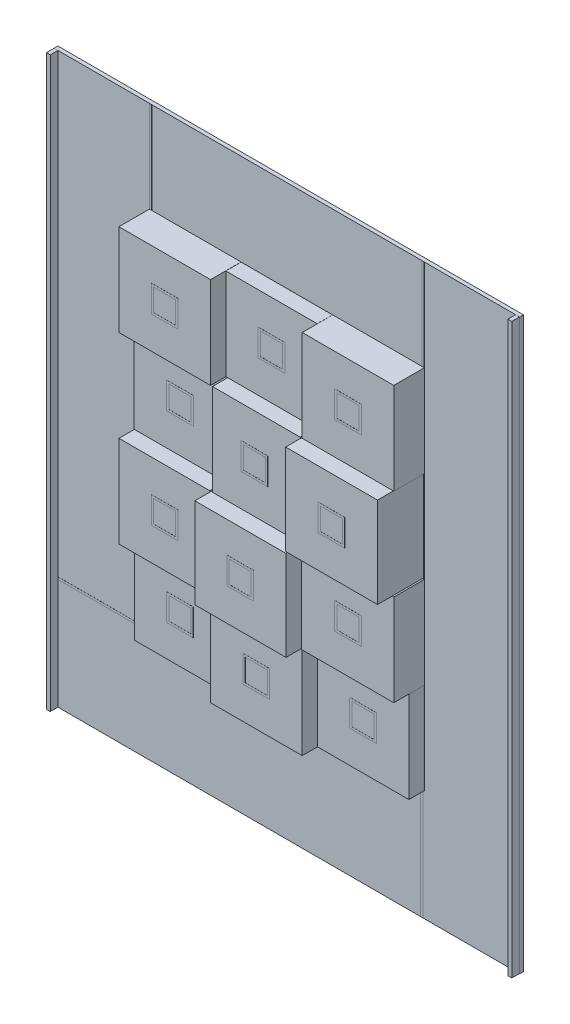
SolidWorks part; units mm, degrees
material "Teak"
ref_plane "Front Plane" through (0, 0, 0) normal (0, 0, 1) x (1, 0, 0)
ref_plane "Top Plane" through (0, 0, 0) normal (0, 1, 0) x (1, 0, 0)
ref_plane "Right Plane" through (0, 0, 0) normal (1, 0, 0) x (0, 0, -1)
sketch "Sketch1" plane through (0, 0, 0) normal (0, 0, 1) x (1, 0, 0)
  line L1 (-2918.6486, 3349.1441) -> (3181.3514, 3349.1441)
  line L2 (-2918.6486, 3349.1441) -> (-2918.6486, -4100.8559)
  line L3 (-2918.6486, -4100.8559) -> (3181.3514, -4100.8559)
  line L4 (3181.3514, 3349.1441) -> (3181.3514, -4100.8559)
  dimension "D1" = 7450
  dimension "D2" = 6100
extrude "Boss-Extrude1" add sketch "Sketch1" along normal blind 50
sketch "Sketch5" plane through (0, 0, 50) normal (0, 0, 1) x (1, 0, 0)
  line L1 (-1668.6486, -2650.8559) -> (1931.3514, -2650.8559)
  line L2 (-1668.6486, -2650.8559) -> (-1668.6486, 2149.1441)
  line L3 (-1668.6486, 2149.1441) -> (1931.3514, 2149.1441)
  line L4 (1931.3514, -2650.8559) -> (1931.3514, 2149.1441)
  line L8 (-1618.6486, -2600.8559) -> (-1618.6486, 2099.1441)
  line L9 (-1618.6486, 2099.1441) -> (1881.3514, 2099.1441)
  line L10 (1881.3514, -2600.8559) -> (1881.3514, 2099.1441)
  line L11 (-1618.6486, -2600.8559) -> (1881.3514, -2600.8559)
  dimension "D1" = 3600
  dimension "D2" = 4800
  dimension "D3" = 50
extrude "Boss-Extrude6" add sketch "Sketch5" along normal blind 1
sketch "Sketch7" plane through (0, 0, 50) normal (0, 0, 1) x (1, 0, 0)
  line L0 (-1668.6486, -2650.8559) -> (1931.3514, -2650.8559) construction
  line L1 (-1668.6486, 2149.1441) -> (-468.6486, 2149.1441)
  line L2 (-1668.6486, 2149.1441) -> (-1668.6486, 949.1441)
  line L3 (-1668.6486, 949.1441) -> (-468.6486, 949.1441)
  line L4 (-468.6486, 2149.1441) -> (-468.6486, 949.1441)
  line L5 (1931.3514, 2149.1441) -> (731.3514, 2149.1441)
  line L6 (1931.3514, 2149.1441) -> (1931.3514, 949.1441)
  line L7 (1931.3514, 949.1441) -> (731.3514, 949.1441)
  line L8 (731.3514, 2149.1441) -> (731.3514, 949.1441)
  line L9 (-443.6486, 949.1441) -> (706.3514, 949.1441)
  line L10 (-443.6486, 949.1441) -> (-443.6486, -250.8559)
  line L11 (-443.6486, -250.8559) -> (706.3514, -250.8559)
  line L12 (706.3514, 949.1441) -> (706.3514, -250.8559)
  line L13 (-468.6486, -2650.8559) -> (731.3514, -2650.8559)
  line L14 (-468.6486, -2650.8559) -> (-468.6486, -1450.8559)
  line L15 (-468.6486, -1450.8559) -> (731.3514, -1450.8559)
  line L16 (731.3514, -2650.8559) -> (731.3514, -1450.8559)
  line L17 (1931.3514, -2650.8559) -> (1931.3514, 2149.1441) construction
  line L18 (-1668.6486, 2149.1441) -> (-1668.6486, -2650.8559) construction
  line L19 (-1668.6486, -250.8559) -> (-478.6486, -250.8559)
  line L20 (-1668.6486, -250.8559) -> (-1668.6486, -1450.8559)
  line L21 (-1668.6486, -1450.8559) -> (-478.6486, -1450.8559)
  line L22 (-478.6486, -250.8559) -> (-478.6486, -1450.8559)
  line L24 (1931.3514, -250.8559) -> (721.3514, -250.8559)
  line L25 (1931.3514, -250.8559) -> (1931.3514, -1450.8559)
  line L26 (1931.3514, -1450.8559) -> (721.3514, -1450.8559)
  line L27 (721.3514, -250.8559) -> (721.3514, -1450.8559)
  line M34 (1931.3514, -2650.8559) -> (-1668.6486, -2650.8559)
  line M35 (-1668.6486, -2650.8559) -> (-1668.6486, 2149.1441)
  line M36 (-1668.6486, 2149.1441) -> (1931.3514, 2149.1441)
  line M37 (1931.3514, 2149.1441) -> (1931.3514, -2650.8559)
  dimension "D1" = 1200
  dimension "D2" = 1200
  dimension "D3" = 1200
  dimension "D4" = 1200
  dimension "D5" = 0
  dimension "D6" = 1200
  dimension "D7" = 1150
  dimension "D8" = 25
  dimension "D9" = 1200
  dimension "D10" = 1200
  dimension "D11" = 1200
  dimension "D12" = 1190
  dimension "D13" = 1200
  dimension "D14" = 1200
  dimension "D15" = 1210
extrude "Boss-Extrude11" add sketch "Sketch7" along normal blind 400 contours L4 L3 M36 M35 | L8 L7 M36 M37 | L12 L9 L10 L11 | L22 L19 L21 M35 | L16 L15 L14 M34 | L24 L27 L15 L26 M37
sketch "Sketch10" plane through (0, 0, 51) normal (0, 0, 1) x (1, 0, 0)
  line L0 (-468.6486, -2600.8559) -> (-468.6486, -1450.8559) construction
  line L1 (-1664.9685, -1454.3725) -> (-471.6486, -1454.3725)
  line L2 (-1664.9685, -1454.3725) -> (-1664.9685, -2638.6722)
  line L3 (-1664.9685, -2638.6722) -> (-471.6486, -2638.6722)
  line L4 (-471.6486, -1454.3725) -> (-471.6486, -2638.6722)
  dimension "D1" = 1184.2997
  dimension "D2" = 1193.3199
  dimension "D3" = 3
extrude "Boss-Extrude13" add sketch "Sketch10" along normal blind 200
sketch "Sketch11" plane through (0, 0, 51) normal (0, 0, 1) x (1, 0, 0)
  line L1 (1928.9649, -1452.6084) -> (732.4691, -1452.6084)
  line L2 (1928.9649, -1452.6084) -> (1928.9649, -2649.4734)
  line L3 (1928.9649, -2649.4734) -> (732.4691, -2649.4734)
  line L4 (732.4691, -1452.6084) -> (732.4691, -2649.4734)
extrude "Boss-Extrude14" add sketch "Sketch11" along normal blind 200
sketch "Sketch12" plane through (0, 0, 51) normal (0, 0, 1) x (1, 0, 0)
  line L1 (-1667.8441, 947.8926) -> (-451.0551, 947.8926)
  line L2 (-1667.8441, 947.8926) -> (-1667.8441, -247.8776)
  line L3 (-1667.8441, -247.8776) -> (-451.0551, -247.8776)
  line L4 (-451.0551, 947.8926) -> (-451.0551, -247.8776)
  line L5 (-467.4826, 2148.0254) -> (729.0204, 2148.0254)
  line L6 (-467.4826, 2148.0254) -> (-467.4826, 949.7722)
  line L7 (-467.4826, 949.7722) -> (729.0204, 949.7722)
  line L8 (729.0204, 2148.0254) -> (729.0204, 949.7722)
extrude "Boss-Extrude15" add sketch "Sketch12" along normal blind 200
sketch "Sketch14" plane through (0, 0, 51) normal (0, 0, 1) x (1, 0, 0)
  line L0 (-478.6486, -250.8559) -> (-478.6486, -1450.8559) construction
  line L1 (715.7522, -242.2942) -> (1919.2918, -242.2942)
  line L2 (715.7522, -242.2942) -> (715.7522, 942.7075)
  line L3 (715.7522, 942.7075) -> (1919.2918, 942.7075)
  line L4 (1919.2918, -242.2942) -> (1919.2918, 942.7075)
  line L5 (720.7186, -261.9442) -> (-473.6486, -261.9442)
  line L6 (720.7186, -261.9442) -> (720.7186, -1441.1949)
  line L7 (720.7186, -1441.1949) -> (-473.6486, -1441.1949)
  line L8 (-473.6486, -261.9442) -> (-473.6486, -1441.1949)
  dimension "D1" = 1194.3673
  dimension "D2" = 5
extrude "Boss-Extrude17" add sketch "Sketch14" along normal blind 600
sketch "Sketch15" plane through (0, 0, 450) normal (0, 0, 1) x (1, 0, 0)
  line L0 (-451.0551, 947.8926) -> (-1667.8441, 947.8926) construction
  line L1 (-1243.6486, 1722.8926) -> (-893.6486, 1722.8926)
  line L2 (-1243.6486, 1722.8926) -> (-1243.6486, 1372.8926)
  line L3 (-1243.6486, 1372.8926) -> (-893.6486, 1372.8926)
  line L4 (-893.6486, 1722.8926) -> (-893.6486, 1372.8926)
  line L5 (-1668.6486, 949.1441) -> (-1668.6486, 2149.1441) construction
  line L7 (-1213.6486, 1692.8926) -> (-1213.6486, 1402.8926)
  line L8 (-1213.6486, 1402.8926) -> (-923.6486, 1402.8926)
  line L9 (-923.6486, 1692.8926) -> (-923.6486, 1402.8926)
  line L10 (-1213.6486, 1692.8926) -> (-923.6486, 1692.8926)
  dimension "D1" = 350
  dimension "D2" = 350
  dimension "D3" = 425
  dimension "D4" = 425
  dimension "D5" = 30
extrude "Boss-Extrude18" add sketch "Sketch15" along normal blind 1
sketch "Sketch16" plane through (0, 0, 450) normal (0, 0, 1) x (1, 0, 0)
  line L0 (-443.6486, 949.1441) -> (706.3514, 949.1441) construction
  line L1 (1156.3514, 1724.1441) -> (1506.3514, 1724.1441)
  line L2 (1156.3514, 1724.1441) -> (1156.3514, 1374.1441)
  line L3 (1156.3514, 1374.1441) -> (1506.3514, 1374.1441)
  line L4 (1506.3514, 1724.1441) -> (1506.3514, 1374.1441)
  line L5 (-68.6486, 524.1441) -> (281.3514, 524.1441)
  line L6 (-68.6486, 524.1441) -> (-68.6486, 174.1441)
  line L7 (-68.6486, 174.1441) -> (281.3514, 174.1441)
  line L8 (281.3514, 524.1441) -> (281.3514, 174.1441)
  line L9 (1156.3514, -675.8559) -> (1506.3514, -675.8559)
  line L10 (1156.3514, -675.8559) -> (1156.3514, -1025.8559)
  line L11 (1156.3514, -1025.8559) -> (1506.3514, -1025.8559)
  line L12 (1506.3514, -675.8559) -> (1506.3514, -1025.8559)
  line L13 (-43.6486, -1875.8559) -> (306.3514, -1875.8559)
  line L14 (-43.6486, -1875.8559) -> (-43.6486, -2225.8559)
  line L15 (-43.6486, -2225.8559) -> (306.3514, -2225.8559)
  line L16 (306.3514, -1875.8559) -> (306.3514, -2225.8559)
  line L17 (-1243.6486, -675.8559) -> (-893.6486, -675.8559)
  line L18 (-1243.6486, -675.8559) -> (-1243.6486, -1025.8559)
  line L19 (-1243.6486, -1025.8559) -> (-893.6486, -1025.8559)
  line L20 (-893.6486, -675.8559) -> (-893.6486, -1025.8559)
  line L21 (706.3514, 949.1441) -> (706.3514, -250.8559) construction
  line L22 (1931.3514, 949.1441) -> (731.3514, 949.1441) construction
  line L23 (731.3514, 2149.1441) -> (731.3514, 949.1441) construction
  line L24 (-1668.6486, -1450.8559) -> (-478.6486, -1450.8559) construction
  line L25 (-1668.6486, 2149.1441) -> (-1668.6486, -2650.8559) construction
  line L26 (1881.3514, -250.8559) -> (721.3514, -250.8559) construction
  line L27 (1931.3514, -250.8559) -> (1931.3514, -1450.8559) construction
  line L28 (731.3514, -2650.8559) -> (-468.6486, -2650.8559) construction
  line L29 (731.3514, -2600.8559) -> (731.3514, -1450.8559) construction
  line L30 (-13.6486, -1905.8559) -> (276.3514, -1905.8559)
  line L31 (276.3514, -1905.8559) -> (276.3514, -2195.8559)
  line L32 (-13.6486, -2195.8559) -> (276.3514, -2195.8559)
  line L33 (-13.6486, -1905.8559) -> (-13.6486, -2195.8559)
  line L34 (1186.3514, -705.8559) -> (1186.3514, -995.8559)
  line L35 (1186.3514, -995.8559) -> (1476.3514, -995.8559)
  line L36 (1476.3514, -705.8559) -> (1476.3514, -995.8559)
  line L37 (1186.3514, -705.8559) -> (1476.3514, -705.8559)
  line L38 (-38.6486, 204.1441) -> (251.3514, 204.1441)
  line L39 (251.3514, 494.1441) -> (251.3514, 204.1441)
  line L40 (-38.6486, 494.1441) -> (251.3514, 494.1441)
  line L41 (-38.6486, 494.1441) -> (-38.6486, 204.1441)
  line L42 (-1213.6486, -705.8559) -> (-923.6486, -705.8559)
  line L43 (-923.6486, -705.8559) -> (-923.6486, -995.8559)
  line L44 (-1213.6486, -995.8559) -> (-923.6486, -995.8559)
  line L45 (-1213.6486, -705.8559) -> (-1213.6486, -995.8559)
  line L46 (1186.3514, 1404.1441) -> (1476.3514, 1404.1441)
  line L47 (1476.3514, 1694.1441) -> (1476.3514, 1404.1441)
  line L48 (1186.3514, 1694.1441) -> (1476.3514, 1694.1441)
  line L49 (1186.3514, 1694.1441) -> (1186.3514, 1404.1441)
  dimension "D1" = 350
  dimension "350" = 350
  dimension "D2" = 350
  dimension "D3" = 350
  dimension "D4" = 350
  dimension "D5" = 350
  dimension "D6" = 350
  dimension "D7" = 350
  dimension "D8" = 350
  dimension "D9" = 350
  dimension "D10" = 425
  dimension "D11" = 425
  dimension "D12" = 425
  dimension "D13" = 425
  dimension "D14" = 425
  dimension "D15" = 425
  dimension "D16" = 425
  dimension "D17" = 425
  dimension "D18" = 425
  dimension "D19" = 425
  dimension "D20" = 30
extrude "Boss-Extrude19" add sketch "Sketch16" along normal blind 1
sketch "Sketch17" plane through (0, 0, 251) normal (0, 0, 1) x (1, 0, 0)
  line L0 (-468.6486, 949.1441) -> (-1618.6486, 949.1441) construction
  line L1 (-42.4826, 1724.1441) -> (307.5174, 1724.1441)
  line L2 (-42.4826, 1724.1441) -> (-42.4826, 1374.1441)
  line L3 (-42.4826, 1374.1441) -> (307.5174, 1374.1441)
  line L4 (307.5174, 1724.1441) -> (307.5174, 1374.1441)
  line L5 (-1242.8441, 524.1441) -> (-892.8441, 524.1441)
  line L6 (-1242.8441, 524.1441) -> (-1242.8441, 174.1441)
  line L7 (-1242.8441, 174.1441) -> (-892.8441, 174.1441)
  line L8 (-892.8441, 524.1441) -> (-892.8441, 174.1441)
  line L9 (-1243.6486, -1875.8559) -> (-893.6486, -1875.8559)
  line L10 (-1243.6486, -1875.8559) -> (-1243.6486, -2225.8559)
  line L11 (-1243.6486, -2225.8559) -> (-893.6486, -2225.8559)
  line L12 (-893.6486, -1875.8559) -> (-893.6486, -2225.8559)
  line L13 (1156.3514, -1875.8559) -> (1506.3514, -1875.8559)
  line L14 (1156.3514, -1875.8559) -> (1156.3514, -2225.8559)
  line L15 (1156.3514, -2225.8559) -> (1506.3514, -2225.8559)
  line L16 (1506.3514, -1875.8559) -> (1506.3514, -2225.8559)
  line L17 (-1667.8441, 947.8926) -> (-1667.8441, -247.8776) construction
  line L18 (-1618.6486, -1450.8559) -> (-478.6486, -1450.8559) construction
  line L19 (-1668.6486, 2149.1441) -> (-1668.6486, -2650.8559) construction
  line L20 (731.3514, -1450.8559) -> (1931.3514, -1450.8559) construction
  line L21 (1931.3514, -2650.8559) -> (1931.3514, 2149.1441) construction
  line L22 (-443.6486, 949.1441) -> (706.3514, 949.1441) construction
  line L23 (-467.4826, 2148.0254) -> (-467.4826, 949.7722) construction
  line L24 (-12.4826, 1694.1441) -> (277.5174, 1694.1441)
  line L25 (277.5174, 1694.1441) -> (277.5174, 1404.1441)
  line L26 (-12.4826, 1404.1441) -> (277.5174, 1404.1441)
  line L27 (-12.4826, 1694.1441) -> (-12.4826, 1404.1441)
  line L28 (-1212.8441, 494.1441) -> (-922.8441, 494.1441)
  line L29 (-922.8441, 494.1441) -> (-922.8441, 204.1441)
  line L30 (-1212.8441, 204.1441) -> (-922.8441, 204.1441)
  line L31 (-1212.8441, 494.1441) -> (-1212.8441, 204.1441)
  line L32 (-1213.6486, -1905.8559) -> (-923.6486, -1905.8559)
  line L33 (-923.6486, -1905.8559) -> (-923.6486, -2195.8559)
  line L34 (-1213.6486, -2195.8559) -> (-923.6486, -2195.8559)
  line L35 (-1213.6486, -1905.8559) -> (-1213.6486, -2195.8559)
  line L36 (1186.3514, -1905.8559) -> (1476.3514, -1905.8559)
  line L37 (1476.3514, -1905.8559) -> (1476.3514, -2195.8559)
  line L38 (1186.3514, -2195.8559) -> (1476.3514, -2195.8559)
  line L39 (1186.3514, -1905.8559) -> (1186.3514, -2195.8559)
  dimension "D1" = 350
  dimension "D2" = 350
  dimension "D3" = 350
  dimension "D4" = 350
  dimension "D5" = 350
  dimension "D6" = 350
  dimension "D7" = 350
  dimension "D8" = 350
  dimension "D9" = 425
  dimension "D10" = 425
  dimension "D11" = 425
  dimension "D12" = 425
  dimension "D13" = 425
  dimension "D14" = 425
  dimension "D15" = 425
  dimension "D16" = 425
  dimension "D17" = 30
extrude "Boss-Extrude20" add sketch "Sketch17" along normal blind 1
sketch "Sketch18" plane through (0, 0, 651) normal (0, 0, 1) x (1, 0, 0)
  line L1 (-53.6486, -666.1949) -> (296.3514, -666.1949)
  line L2 (-53.6486, -666.1949) -> (-53.6486, -1016.1949)
  line L3 (-53.6486, -1016.1949) -> (296.3514, -1016.1949)
  line L4 (296.3514, -666.1949) -> (296.3514, -1016.1949)
  line L5 (1140.7522, 532.7058) -> (1490.7522, 532.7058)
  line L6 (1140.7522, 532.7058) -> (1140.7522, 182.7058)
  line L7 (1140.7522, 182.7058) -> (1490.7522, 182.7058)
  line L8 (1490.7522, 532.7058) -> (1490.7522, 182.7058)
  line L9 (-473.6486, -1441.1949) -> (720.7186, -1441.1949) construction
  line L10 (-478.6486, -250.8559) -> (-478.6486, -1450.8559) construction
  line L11 (715.7522, -242.2942) -> (1919.2918, -242.2942) construction
  line L12 (715.7522, 942.7075) -> (715.7522, -242.2942) construction
  line L13 (-23.6486, -696.1949) -> (266.3514, -696.1949)
  line L14 (266.3514, -696.1949) -> (266.3514, -986.1949)
  line L15 (-23.6486, -986.1949) -> (266.3514, -986.1949)
  line L16 (-23.6486, -696.1949) -> (-23.6486, -986.1949)
  line L17 (1170.7522, 502.7058) -> (1460.7522, 502.7058)
  line L18 (1460.7522, 502.7058) -> (1460.7522, 212.7058)
  line L19 (1170.7522, 212.7058) -> (1460.7522, 212.7058)
  line L20 (1170.7522, 502.7058) -> (1170.7522, 212.7058)
  dimension "D1" = 350
  dimension "D2" = 350
  dimension "D3" = 350
  dimension "D4" = 350
  dimension "D5" = 425
  dimension "D6" = 425
  dimension "D7" = 425
  dimension "D8" = 425
  dimension "D9" = 30
extrude "Boss-Extrude21" add sketch "Sketch18" along normal blind 1
sketch "Sketch20" plane through (0, 0, 50) normal (0, 0, 1) x (1, 0, 0)
  line L1 (-2918.3825, 3348.9076) -> (-2868.3825, 3348.9076)
  line L2 (-2918.3825, 3348.9076) -> (-2918.3825, -4100.7667)
  line L3 (-2918.3825, -4100.7667) -> (-2868.3825, -4100.7667)
  line L4 (-2868.3825, 3348.9076) -> (-2868.3825, -4100.7667)
  dimension "D1" = 50
extrude "Boss-Extrude22" add sketch "Sketch20" along normal blind 100
sketch "Sketch21" plane through (0, 0, 50) normal (0, 0, 1) x (1, 0, 0)
  line L1 (3176.8377, 3348.3518) -> (3126.8377, 3348.3518)
  line L2 (3176.8377, 3348.3518) -> (3176.8377, -4100.4594)
  line L3 (3176.8377, -4100.4594) -> (3126.8377, -4100.4594)
  line L4 (3126.8377, 3348.3518) -> (3126.8377, -4100.4594)
  dimension "D1" = 50
extrude "Boss-Extrude23" add sketch "Sketch21" along normal blind 100
sketch "Sketch23" plane through (0, 0, 50) normal (0, 0, 1) x (1, 0, 0)
  line L5 (-1668.9146, -2650.8857) -> (-2867.9192, -2650.8857)
  line L6 (-1668.9146, -2650.8857) -> (-1668.9146, -2620.8857)
  line L7 (-1668.9146, -2620.8857) -> (-2867.9192, -2620.8857)
  line L8 (-2867.9192, -2650.8857) -> (-2867.9192, -2620.8857)
  line L9 (1913.7853, -2650.9601) -> (1883.7853, -2650.9601)
  line L10 (1913.7853, -2650.9601) -> (1913.7853, -4100.3107)
  line L11 (1913.7853, -4100.3107) -> (1883.7853, -4100.3107)
  line L12 (1883.7853, -2650.9601) -> (1883.7853, -4100.3107)
  line L13 (-1668.6538, 2149.1784) -> (-1638.6538, 2149.1784)
  line L14 (-1668.6538, 2149.1784) -> (-1668.6538, 3349.1096)
  line L15 (-1668.6538, 3349.1096) -> (-1638.6538, 3349.1096)
  line L16 (-1638.6538, 2149.1784) -> (-1638.6538, 3349.1096)
  line L17 (1931.3514, 2149.1441) -> (1901.3514, 2149.1441)
  line L18 (1931.3514, 2149.1441) -> (1931.3514, 3349.1394)
  line L19 (1931.3514, 3349.1394) -> (1901.3514, 3349.1394)
  line L20 (1901.3514, 2149.1441) -> (1901.3514, 3349.1394)
  dimension "D1" = 30
  dimension "D2" = 30
  dimension "D3" = 30
  dimension "D4" = 30
  dimension "D5" = 0
extrude "Boss-Extrude25" add sketch "Sketch23" along normal blind 1
